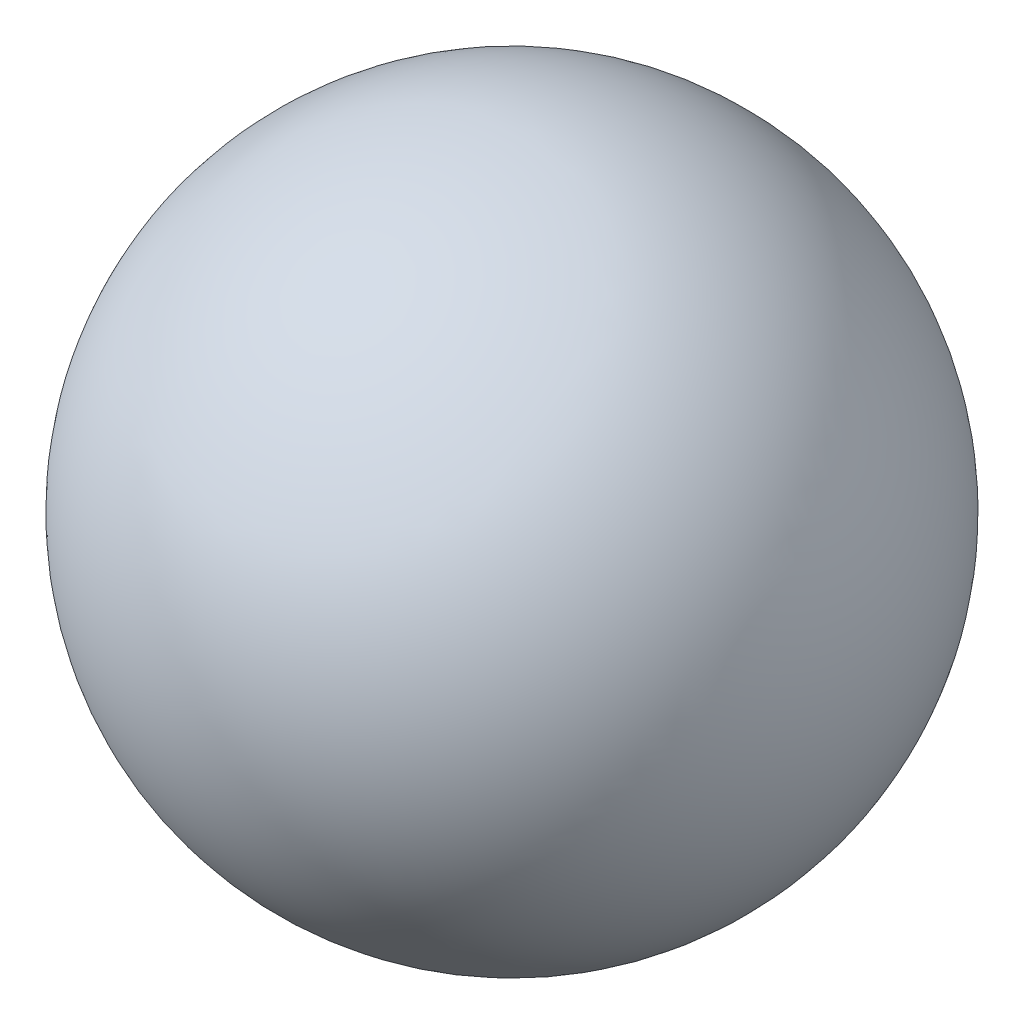
SolidWorks part; units mm, degrees
ref_plane "Front Plane" through (0, 0, 0) normal (0, 0, 1) x (1, 0, 0)
ref_plane "Top Plane" through (0, 0, 0) normal (0, 1, 0) x (1, 0, 0)
ref_plane "Right Plane" through (0, 0, 0) normal (1, 0, 0) x (0, 0, -1)
sketch "Sketch1" plane through (0, 0, 0) normal (0, 0, 1) x (1, 0, 0)
  line L0 (-120, 0) -> (120, 0)
  arc A0 (120, 0) -> (-120, 0) centre (0, 0) cw
  point P4 (0, 0)
  point P5 (0, 0)
  point P6 (0, 0)
  point P7 (0, 0)
  point P8 (0, 0)
  point P9 (0, 0)
  dimension "D1" = 240
revolve "Revolve1" add sketch "Sketch1" angle 360 about L0
